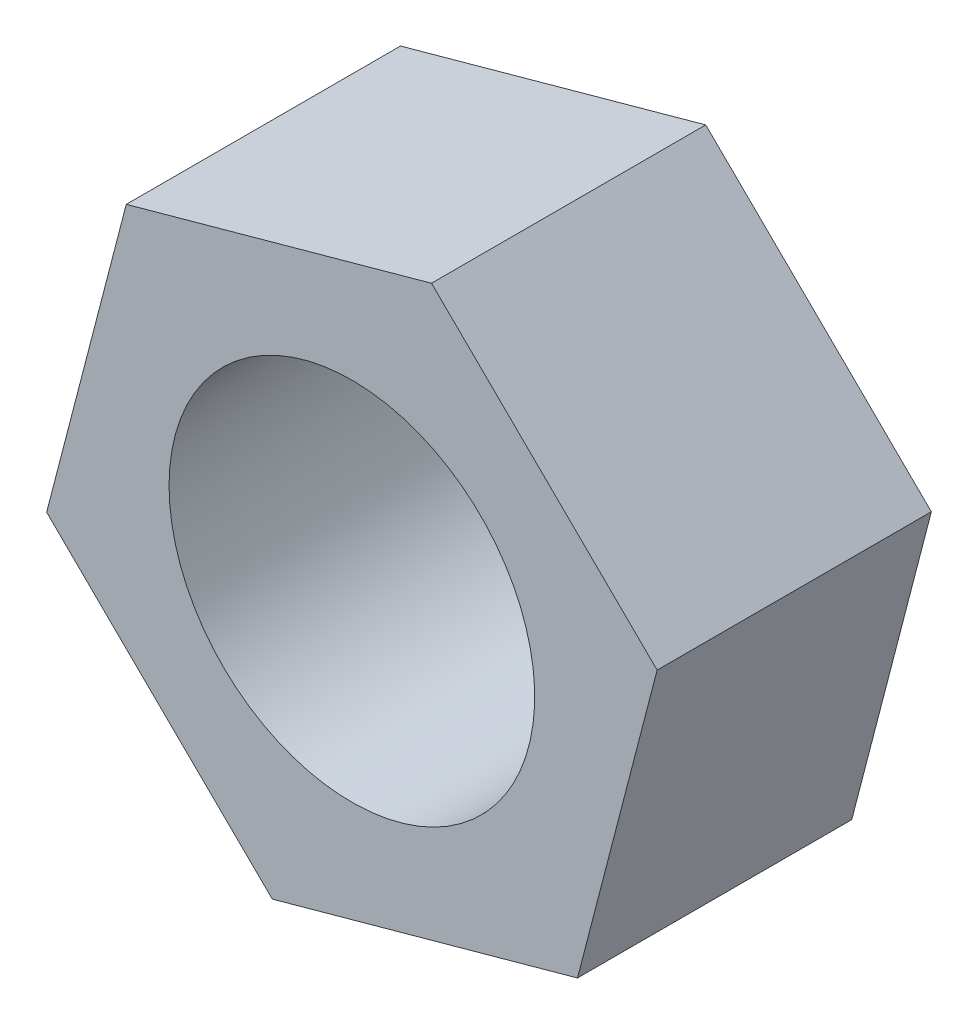
SolidWorks part; units mm, degrees
ref_plane "Front Plane" through (0, 0, 0) normal (0, 0, 1) x (1, 0, 0)
ref_plane "Top Plane" through (0, 0, 0) normal (0, 1, 0) x (1, 0, 0)
ref_plane "Right Plane" through (0, 0, 0) normal (1, 0, 0) x (0, 0, -1)
sketch "Sketch1" plane through (0, 0, 0) normal (0, 0, 1) x (1, 0, 0)
  line L1 (2.4681, -2.4307) -> (3.3391, 0.9221)
  line L2 (3.3391, 0.9221) -> (0.871, 3.3528)
  line L3 (0.871, 3.3528) -> (-2.4681, 2.4307)
  line L4 (-2.4681, 2.4307) -> (-3.3391, -0.9221)
  line L5 (-3.3391, -0.9221) -> (-0.871, -3.3528)
  line L6 (-0.871, -3.3528) -> (2.4681, -2.4307)
  circle A0 centre (0, 0) radius 3 construction
  dimension "D1" = 6
extrude "Boss-Extrude1" add sketch "Sketch1" along normal blind 3
sketch "Sketch2" plane through (0, 0, 0) normal (0, 0, -1) x (-1, 0, 0)
  circle A0 centre (0, 0) radius 2
  dimension "D1" = 4
extrude "Cut-Extrude1" cut sketch "Sketch2" against normal blind 3
